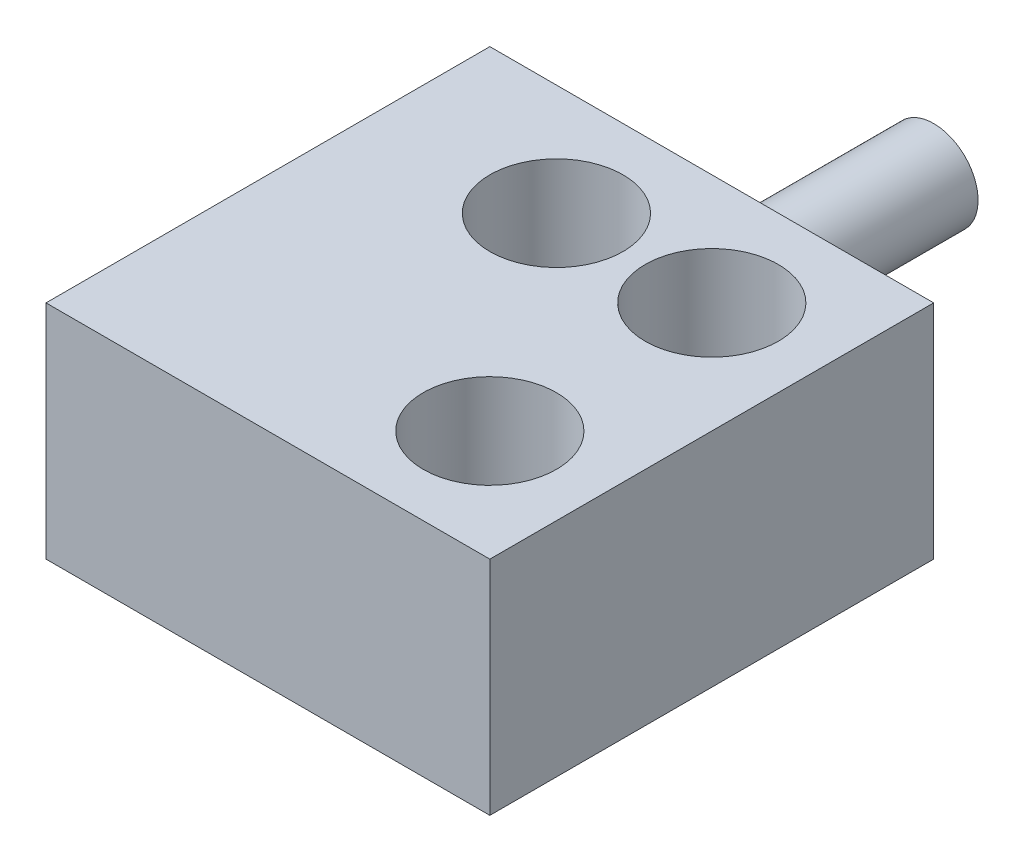
SolidWorks part; units mm, degrees
ref_plane "前视基准面" through (0, 0, 0) normal (0, 0, 1) x (1, 0, 0)
ref_plane "上视基准面" through (0, 0, 0) normal (0, 1, 0) x (1, 0, 0)
ref_plane "右视基准面" through (0, 0, 0) normal (1, 0, 0) x (0, 0, -1)
sketch "草图1" plane through (0, 0, 0) normal (0, 1, 0) x (1, 0, 0)
  line L1 (0, 0) -> (10, 0)
  line L2 (0, 0) -> (0, 10)
  line L3 (0, 10) -> (10, 10)
  line L4 (10, 0) -> (10, 10)
  circle A0 centre (7.5, 7.5) radius 1.5
  circle A1 centre (7.5, 2.5) radius 1.5
  circle A2 centre (4, 7.5) radius 1.5
  dimension "D5" = 3
  dimension "D1" = 10
  dimension "D2" = 10
  dimension "D3" = 3.5
  dimension "D4" = 5
  dimension "D6" = 4
  dimension "D7" = 2.5
extrude "凸台-拉伸1" add sketch "草图1" along normal blind 5
sketch "草图2" plane through (0, 0, -10) normal (0, 0, -1) x (-1, 0, 0)
  line L0 (-10, 5) -> (0, 5) construction
  line L1 (0, 5) -> (0, 0) construction
  circle A0 centre (-5, 2.5) radius 1
  point P4 (-5, 5)
  dimension "D1" = 2
  dimension "D2" = 2.5
  dimension "D3" = 5
extrude "凸台-拉伸2" add sketch "草图2" along normal blind 5
